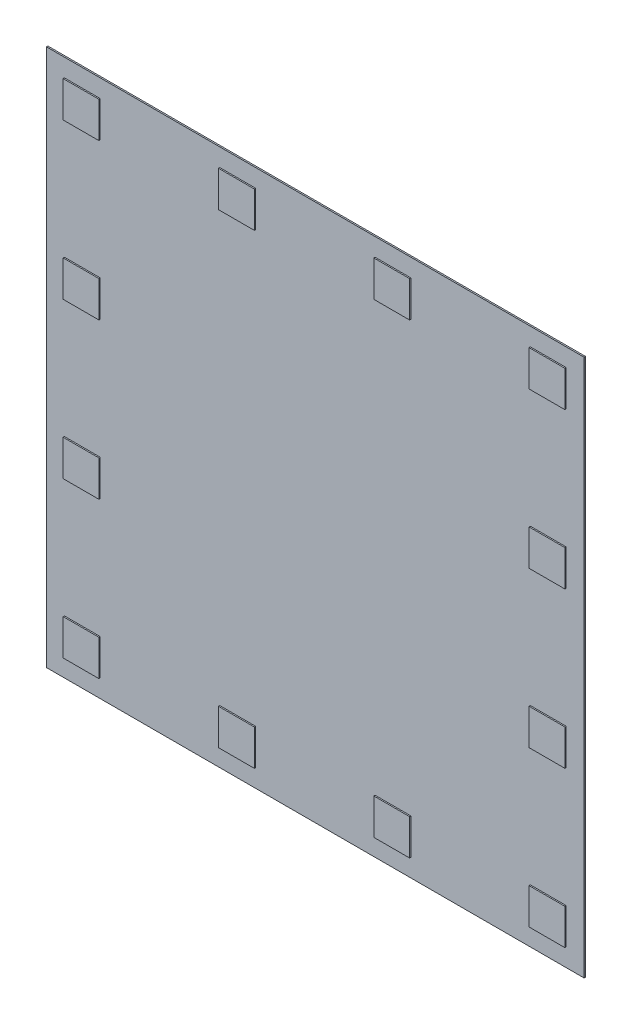
SolidWorks part; units mm, degrees
ref_plane "정면" through (0, 0, 0) normal (0, 0, 1) x (1, 0, 0)
ref_plane "윗면" through (0, 0, 0) normal (0, 1, 0) x (1, 0, 0)
ref_plane "우측면" through (0, 0, 0) normal (1, 0, 0) x (0, 0, -1)
sketch "스케치1" plane through (0, 0, 0) normal (0, 0, 1) x (1, 0, 0)
  line L1 (-150, -150) -> (150, -150)
  line L2 (-150, -150) -> (-150, 150)
  line L3 (-150, 150) -> (150, 150)
  line L4 (150, -150) -> (150, 150)
  line L5 (-150, -150) -> (150, 150) construction
  line L6 (-150, 150) -> (150, -150) construction
  point P1 (0, 0)
  dimension "D1" = 300
  dimension "D2" = 300
extrude "보스-돌출1" add sketch "스케치1" along normal blind 0.1
sketch "스케치2" plane through (0, 0, 0.1) normal (0, 0, 1) x (1, 0, 0)
  line L0 (-53.3333, 140) -> (-53.3333, 120)
  line L1 (-140, 140) -> (-120, 140)
  line L2 (-140, 140) -> (-140, 120)
  line L3 (-140, 120) -> (-120, 120)
  line L4 (-120, 140) -> (-120, 120)
  line L5 (-53.3333, 140) -> (-33.3333, 140)
  line L6 (-33.3333, 140) -> (-33.3333, 120)
  line L7 (-53.3333, 120) -> (-33.3333, 120)
  line L8 (33.3333, 140) -> (33.3333, 120)
  line L9 (33.3333, 140) -> (53.3333, 140)
  line L10 (53.3333, 140) -> (53.3333, 120)
  line L11 (33.3333, 120) -> (53.3333, 120)
  line L12 (120, 140) -> (120, 120)
  line L13 (120, 140) -> (140, 140)
  line L14 (140, 140) -> (140, 120)
  line L15 (120, 120) -> (140, 120)
  line L16 (-140, 53.3333) -> (-140, 33.3333)
  line L17 (-140, 53.3333) -> (-120, 53.3333)
  line L18 (-120, 53.3333) -> (-120, 33.3333)
  line L19 (-140, 33.3333) -> (-120, 33.3333)
  line L20 (-140, -33.3333) -> (-140, -53.3333)
  line L21 (-140, -33.3333) -> (-120, -33.3333)
  line L22 (-120, -33.3333) -> (-120, -53.3333)
  line L23 (-140, -53.3333) -> (-120, -53.3333)
  line L24 (-140, -120) -> (-140, -140)
  line L25 (-140, -120) -> (-120, -120)
  line L26 (-120, -120) -> (-120, -140)
  line L27 (-140, -140) -> (-120, -140)
  line L28 (120, 53.3333) -> (120, 33.3333)
  line L29 (120, 33.3333) -> (140, 33.3333)
  line L30 (140, 53.3333) -> (140, 33.3333)
  line L31 (120, 53.3333) -> (140, 53.3333)
  line L32 (120, -33.3333) -> (120, -53.3333)
  line L33 (120, -53.3333) -> (140, -53.3333)
  line L34 (140, -33.3333) -> (140, -53.3333)
  line L35 (120, -33.3333) -> (140, -33.3333)
  line L36 (-53.3333, -120) -> (-53.3333, -140)
  line L37 (-53.3333, -140) -> (-33.3333, -140)
  line L38 (-33.3333, -120) -> (-33.3333, -140)
  line L39 (-53.3333, -120) -> (-33.3333, -120)
  line L40 (33.3333, -120) -> (33.3333, -140)
  line L41 (33.3333, -140) -> (53.3333, -140)
  line L42 (53.3333, -120) -> (53.3333, -140)
  line L43 (33.3333, -120) -> (53.3333, -120)
  line L44 (120, -120) -> (120, -140)
  line L45 (120, -140) -> (140, -140)
  line L46 (140, -120) -> (140, -140)
  line L47 (120, -120) -> (140, -120)
  line L48 (0, 0) -> (0, 186.7508) construction
  line L49 (0, 186.7508) -> (0, -214.9581) construction
  line L50 (0, 0) -> (417.5173, 0) construction
  line L51 (417.5173, 0) -> (-355.4147, 0) construction
  line L52 (-33.3333, 140) -> (33.3333, 140) construction
  line L53 (-140, 33.3333) -> (-140, -33.3333) construction
  point P53 (0, 140)
  point P55 (-140, 0)
  dimension "D5" = 20
  dimension "D6" = 140
  dimension "D1" = 4
  dimension "D2" = 4
  dimension "D3" = 3
  dimension "D4" = 4
extrude "보스-돌출2" add sketch "스케치2" along normal blind 0.7
sketch "스케치3" plane through (0, 0, 0) normal (0, 0, -1) x (-1, 0, 0)
  line L1 (-150, -150) -> (150, -150)
  line L2 (-150, -150) -> (-150, 150)
  line L3 (-150, 150) -> (150, 150)
  line L4 (150, -150) -> (150, 150)
extrude "보스-돌출3" add sketch "스케치3" along normal blind 0.7 separate body
